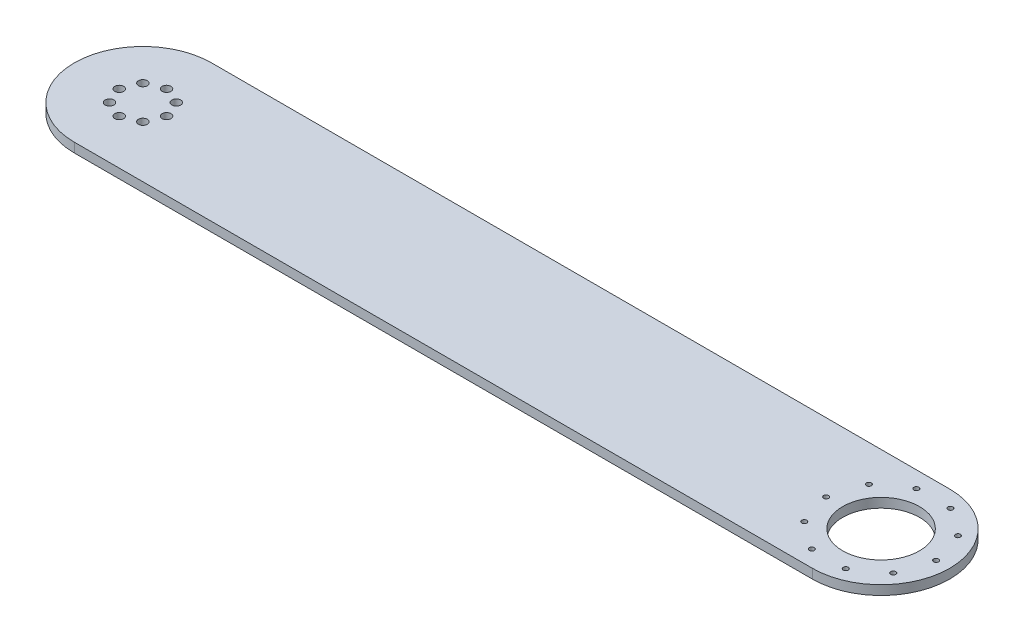
SolidWorks part; units mm, degrees
ref_plane "Front Plane" through (0, 0, 0) normal (0, 0, 1) x (1, 0, 0)
ref_plane "Top Plane" through (0, 0, 0) normal (0, 1, 0) x (1, 0, 0)
ref_plane "Right Plane" through (0, 0, 0) normal (1, 0, 0) x (0, 0, -1)
sketch "Sketch1" plane through (0, 0, 0) normal (0, 1, 0) x (1, 0, 0)
  line L0 (0, 0) -> (500, 0) construction
  line L1 (0, 46.5) -> (500, 46.5)
  line L2 (0, -46.5) -> (500, -46.5)
  arc A0 (0, 46.5) -> (0, -46.5) centre (0, 0) ccw
  arc A1 (500, -46.5) -> (500, 46.5) centre (500, 0) ccw
  circle A2 centre (0, 0) radius 16 construction
  circle A3 centre (-16, 0) radius 3
  circle A4 centre (-11.3137, 11.3137) radius 3
  circle A5 centre (0, 16) radius 3
  circle A6 centre (11.3137, 11.3137) radius 3
  circle A7 centre (16, 0) radius 3
  circle A8 centre (11.3137, -11.3137) radius 3
  circle A27 centre (500, 0) radius 37.25 construction
  circle A28 centre (537.25, 0) radius 1.7
  circle A29 centre (500, 0) radius 37.25 construction
  circle A30 centre (537.25, 0) radius 1.7
  circle A31 centre (530.1359, -21.895) radius 1.7
  circle A32 centre (511.5109, -35.4269) radius 1.7
  circle A33 centre (488.4891, -35.4269) radius 1.7
  circle A34 centre (469.8641, -21.895) radius 1.7
  circle A35 centre (462.75, 0) radius 1.7
  circle A36 centre (469.8641, 21.895) radius 1.7
  circle A37 centre (488.4891, 35.4269) radius 1.7
  circle A38 centre (511.5109, 35.4269) radius 1.7
  circle A39 centre (530.1359, 21.895) radius 1.7
  circle A40 centre (500, 0) radius 26
  circle A41 centre (0, -16) radius 3
  circle A42 centre (-11.3137, -11.3137) radius 3
  point P3 (250, 0)
  point P25 (0, 0)
  point P52 (500, 0)
  point P61 (500, 0)
  dimension "D3" = 32
  dimension "D4" = 6
  dimension "D2" = 74.5
  dimension "D7" = 3.4
  dimension "D8" = 3.4
  dimension "D10" = 52
  dimension "D6" = 46.5
  dimension "D1" = 500
  dimension "D5" = 8
  dimension "D9" = 10
extrude "Boss-Extrude1" add sketch "Sketch1" along normal blind 6.35 contours L2 A1 L1 A0 A40 A39 A38 A37 A36 A35 A34 A33 A32 A31 A28 A8 A7 A6 A5 A4 A3
equation "\"L1L\"=500"
equation "\"D1@Sketch1\"=\"L1L\""
equation "\"L1Thick\"=6.35"
equation "\"D1@Boss-Extrude1\"=\"L1Thick\""
equation "\"Harm-Drive-Outer\"=74.5"
equation "\"D2@Sketch1\"=\"Harm-Drive-Outer\""
